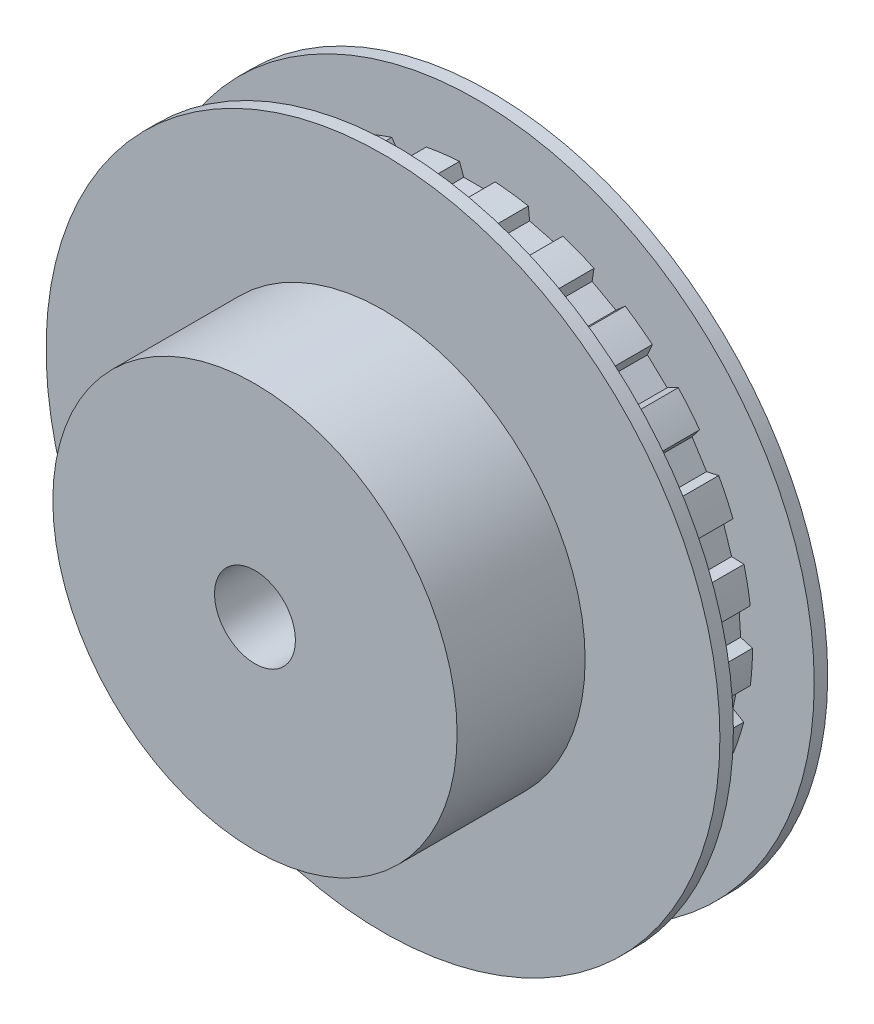
SolidWorks part; units mm, degrees
ref_plane "Front Plane" through (0, 0, 0) normal (0, 0, 1) x (1, 0, 0)
ref_plane "Top Plane" through (0, 0, 0) normal (0, 1, 0) x (1, 0, 0)
ref_plane "Right Plane" through (0, 0, 0) normal (1, 0, 0) x (0, 0, -1)
sketch "Sketch1" plane through (0, 0, 0) normal (0, 0, 1) x (1, 0, 0)
  line L0 (0, 0) -> (0, 20) construction
  line L1 (0, 0) -> (6.1803, 19.0211) construction
  line L6 (-1.3211, 20.375) -> (-1.0481, 19.625)
  line L7 (-1.0481, 19.625) -> (1.0481, 19.625)
  line L8 (1.0481, 19.625) -> (1.3211, 20.375)
  line L9 (1.3211, 20.375) -> (-1.3211, 20.375)
  circle A1 centre (0, 0) radius 20 construction
  point P7 (0, 0)
  dimension "D1" = 40
  dimension "D2" = 18
  dimension "D3" = 0.75
  dimension "D4" = 0.375
  dimension "D5" = 2.6422
  dimension "D6" = 40
sketch "Sketch2" plane through (0, 0, 0) normal (0, 0, 1) x (1, 0, 0)
  circle A0 centre (0, 0) radius 20.4178
extrude "Boss-Extrude1" add sketch "Sketch2" along normal mid plane 6
sketch "Sketch4" plane through (0, 0, 3) normal (0, 0, 1) x (1, 0, 0)
  line L0 (1.0481, 19.625) -> (1.3211, 20.375) construction
  line L1 (-1.3211, 20.375) -> (-1.0481, 19.625) construction
  line L2 (1.0066, 19.511) -> (1.3769, 20.5282)
  line L3 (-1.3768, 20.5281) -> (-1.0066, 19.5109)
  line L4 (-1.3768, 20.5281) -> (1.3769, 20.5282)
  line L5 (-1.0066, 19.5109) -> (1.0066, 19.511)
  line L6 (5.8272, 18.6477) -> (6.4388, 19.5409)
  line L7 (3.7716, 20.2255) -> (3.8772, 19.1483)
  line L8 (3.7716, 20.2255) -> (6.4388, 19.5409)
  line L9 (3.8772, 19.1483) -> (5.8272, 18.6477)
  line L10 (10.2817, 16.6127) -> (11.0961, 17.3257)
  line L11 (8.683, 18.6522) -> (8.5174, 17.5825)
  line L12 (8.683, 18.6522) -> (11.0961, 17.3257)
  line L13 (8.5174, 17.5825) -> (10.2817, 16.6127)
  line L14 (14.09, 13.5338) -> (15.0562, 14.0219)
  line L15 (13.0488, 15.9068) -> (12.6224, 14.9119)
  line L16 (13.0488, 15.9068) -> (15.0562, 14.0219)
  line L17 (12.6224, 14.9119) -> (14.09, 13.5338)
  line L18 (17.0131, 9.6046) -> (18.0703, 9.837)
  line L19 (16.5947, 12.162) -> (15.9343, 11.3044)
  line L20 (16.5947, 12.162) -> (18.0703, 9.837)
  line L21 (15.9343, 11.3044) -> (17.0131, 9.6046)
  line L22 (18.8672, 5.0719) -> (19.949, 5.0341)
  line L23 (19.0979, 7.653) -> (18.2449, 6.9865)
  line L24 (19.0979, 7.653) -> (19.949, 5.0341)
  line L25 (18.2449, 6.9865) -> (18.8672, 5.0719)
  line L26 (19.5358, 0.2204) -> (20.5741, -0.0852)
  line L27 (20.4011, 2.6631) -> (19.4092, 2.2297)
  line L28 (20.4011, 2.6631) -> (20.5741, -0.0852)
  line L29 (19.4092, 2.2297) -> (19.5358, 0.2204)
  line L30 (18.9768, -4.6448) -> (19.9066, -5.1991)
  line L31 (20.4225, -2.4942) -> (19.354, -2.6672)
  line L32 (20.4225, -2.4942) -> (19.9066, -5.1991)
  line L33 (19.354, -2.6672) -> (18.9768, -4.6448)
  line L34 (17.2255, -9.2182) -> (17.9882, -9.9863)
  line L35 (19.1606, -7.4947) -> (18.0826, -7.3965)
  line L36 (19.1606, -7.4947) -> (17.9882, -9.9863)
  line L37 (18.0826, -7.3965) -> (17.2255, -9.2182)
  line L38 (14.3919, -13.2124) -> (14.9396, -14.1461)
  line L39 (16.6948, -12.0242) -> (15.6751, -11.6611)
  line L40 (16.6948, -12.0242) -> (14.9396, -14.1461)
  line L41 (15.6751, -11.6611) -> (14.3919, -13.2124)
  line L42 (10.6539, -16.3765) -> (10.9523, -17.417)
  line L43 (13.18, -15.7983) -> (12.2826, -15.193)
  line L44 (13.18, -15.7983) -> (10.9523, -17.417)
  line L45 (12.2826, -15.193) -> (10.6539, -16.3765)
  line L46 (6.2465, -18.5115) -> (6.2768, -19.5935)
  line L47 (8.837, -18.5797) -> (8.1184, -17.7702)
  line L48 (8.837, -18.5797) -> (6.2768, -19.5935)
  line L49 (8.1184, -17.7702) -> (6.2465, -18.5115)
  line L50 (1.4467, -19.4834) -> (1.2069, -20.5389)
  line L51 (3.9388, -20.1936) -> (3.444, -19.2309)
  line L52 (3.9388, -20.1936) -> (1.2069, -20.5389)
  line L53 (3.444, -19.2309) -> (1.4467, -19.4834)
  line L54 (-3.4441, -19.231) -> (-3.9389, -20.1938)
  line L55 (-1.2069, -20.5388) -> (-1.4467, -19.4832)
  line L56 (-1.2069, -20.5388) -> (-3.9389, -20.1938)
  line L57 (-1.4467, -19.4832) -> (-3.4441, -19.231)
  line L58 (-8.1185, -17.7703) -> (-8.8371, -18.5798)
  line L59 (-6.2768, -19.5934) -> (-6.2465, -18.5114)
  line L60 (-6.2768, -19.5934) -> (-8.8371, -18.5798)
  line L61 (-6.2465, -18.5114) -> (-8.1185, -17.7703)
  line L62 (-12.2827, -15.1931) -> (-13.1801, -15.7984)
  line L63 (-10.9522, -17.4168) -> (-10.6539, -16.3763)
  line L64 (-10.9522, -17.4168) -> (-13.1801, -15.7984)
  line L65 (-10.6539, -16.3763) -> (-12.2827, -15.1931)
  line L66 (-15.6752, -11.6612) -> (-16.6949, -12.0243)
  line L67 (-14.9395, -14.1459) -> (-14.3918, -13.2123)
  line L68 (-14.9395, -14.1459) -> (-16.6949, -12.0243)
  line L69 (-14.3918, -13.2123) -> (-15.6752, -11.6612)
  line L70 (-18.0827, -7.3966) -> (-19.1607, -7.4947)
  line L71 (-17.9881, -9.9862) -> (-17.2254, -9.2181)
  line L72 (-17.9881, -9.9862) -> (-19.1607, -7.4947)
  line L73 (-17.2254, -9.2181) -> (-18.0827, -7.3966)
  line L74 (-19.3541, -2.6672) -> (-20.4226, -2.4941)
  line L75 (-19.9065, -5.199) -> (-18.9767, -4.6448)
  line L76 (-19.9065, -5.199) -> (-20.4226, -2.4941)
  line L77 (-18.9767, -4.6448) -> (-19.3541, -2.6672)
  line L78 (-19.4093, 2.2298) -> (-20.4012, 2.6631)
  line L79 (-20.574, -0.0851) -> (-19.5356, 0.2205)
  line L80 (-20.574, -0.0851) -> (-20.4012, 2.6631)
  line L81 (-19.5356, 0.2205) -> (-19.4093, 2.2298)
  line L82 (-18.245, 6.9866) -> (-19.098, 7.653)
  line L83 (-19.9488, 5.0341) -> (-18.867, 5.0719)
  line L84 (-19.9488, 5.0341) -> (-19.098, 7.653)
  line L85 (-18.867, 5.0719) -> (-18.245, 6.9866)
  line L86 (-15.9343, 11.3045) -> (-16.5948, 12.1621)
  line L87 (-18.0702, 9.837) -> (-17.013, 9.6046)
  line L88 (-18.0702, 9.837) -> (-16.5948, 12.1621)
  line L89 (-17.013, 9.6046) -> (-15.9343, 11.3045)
  line L90 (-12.6224, 14.912) -> (-13.0488, 15.9069)
  line L91 (-15.0561, 14.0218) -> (-14.0899, 13.5338)
  line L92 (-15.0561, 14.0218) -> (-13.0488, 15.9069)
  line L93 (-14.0899, 13.5338) -> (-12.6224, 14.912)
  line L94 (-8.5174, 17.5826) -> (-8.683, 18.6523)
  line L95 (-11.096, 17.3256) -> (-10.2816, 16.6126)
  line L96 (-11.096, 17.3256) -> (-8.683, 18.6523)
  line L97 (-10.2816, 16.6126) -> (-8.5174, 17.5826)
  line L98 (-3.8772, 19.1484) -> (-3.7716, 20.2257)
  line L99 (-6.4387, 19.5407) -> (-5.8271, 18.6476)
  line L100 (-6.4387, 19.5407) -> (-3.7716, 20.2257)
  line L101 (-5.8271, 18.6476) -> (-3.8772, 19.1484)
  point P106 (0, 0)
  dimension "D1" = 25
extrude "Cut-Extrude3" cut sketch "Sketch4" against normal blind 6
sketch "Sketch5" plane through (0, 0, 3) normal (0, 0, 1) x (1, 0, 0)
  circle A0 centre (0, 0) radius 25
  dimension "D1" = 50
extrude "Boss-Extrude2" add sketch "Sketch5" along normal blind 1
mirror "Mirror2" about plane through (0, 0, 0) normal (0, 0, 1) of "Boss-Extrude2"
sketch "Sketch6" plane through (0, 0, 4) normal (0, 0, 1) x (1, 0, 0)
  circle A0 centre (0, 0) radius 15
  dimension "D1" = 30
extrude "Boss-Extrude3" add sketch "Sketch6" along normal blind 9.5
sketch "Sketch8" plane through (0, 0, 13.5) normal (0, 0, 1) x (1, 0, 0)
  circle A0 centre (0, 0) radius 3
  dimension "D1" = 6
extrude "Cut-Extrude4" cut sketch "Sketch8" against normal through all
